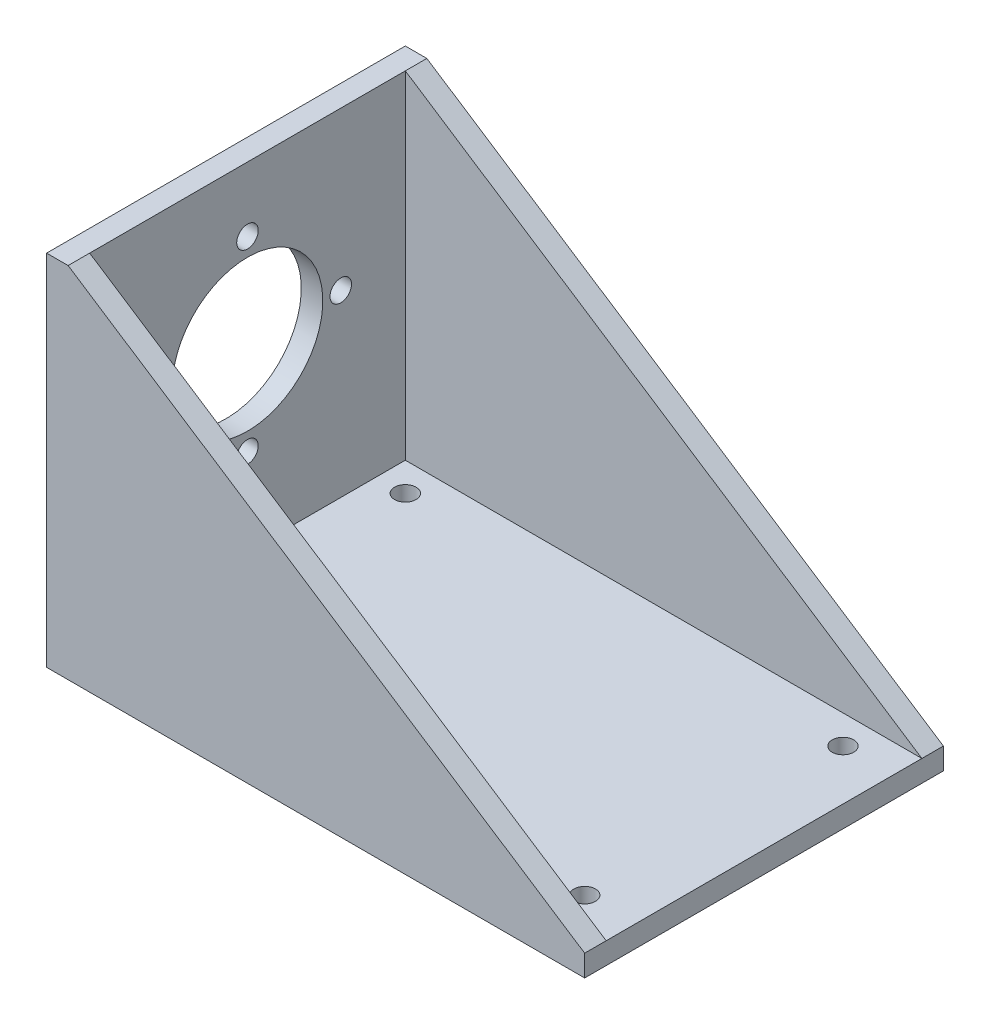
SolidWorks part; units mm, degrees
material "ABS"
ref_plane "Plan de face" through (0, 0, 0) normal (0, 0, 1) x (1, 0, 0)
ref_plane "Plan de dessus" through (0, 0, 0) normal (0, 1, 0) x (1, 0, 0)
ref_plane "Plan de droite" through (0, 0, 0) normal (1, 0, 0) x (0, 0, -1)
sketch "Esquisse1" plane through (0, 0, 0) normal (0, 1, 0) x (1, 0, 0)
  line L1 (0, 0) -> (75, 0)
  line L2 (0, 0) -> (0, 50)
  line L3 (0, 50) -> (75, 50)
  line L4 (75, 0) -> (75, 50)
  dimension "D1" = 50
  dimension "D2" = 75
extrude "Boss.-Extru.1" add sketch "Esquisse1" along normal blind 3
sketch "Esquisse2" plane through (0, 3, 0) normal (0, 1, 0) x (1, 0, 0)
  line L0 (75, 50) -> (0, 50) construction
  line L1 (0, 0) -> (3, 0)
  line L2 (0, 0) -> (0, 50)
  line L3 (0, 50) -> (3, 50)
  line L4 (3, 0) -> (3, 50)
  dimension "D1" = 3
extrude "Boss.-Extru.2" add sketch "Esquisse2" along normal blind 47
sketch "Esquisse3" plane through (0, 0, 0) normal (-1, 0, 0) x (0, 0, 1)
  line L0 (-50, 0) -> (0, 0) construction
  line L1 (0, 50) -> (0, 0) construction
  line L2 (-25, 28) -> (-12, 28) construction
  circle A0 centre (-25, 28) radius 10.5
  circle A1 centre (-12, 28) radius 1.5
  circle A2 centre (-25, 15) radius 1.5
  circle A3 centre (-38, 28) radius 1.5
  circle A4 centre (-25, 41) radius 1.5
  point P17 (-25, 28)
  dimension "D1" = 21
  dimension "D5" = 3
  dimension "D2" = 28
  dimension "D3" = 25
  dimension "D4" = 13
  dimension "D6" = 4
extrude "Enlèv. mat.-Extru.1" cut sketch "Esquisse3" against normal blind 3
sketch "Esquisse4" plane through (0, 0, 0) normal (0, 0, 1) x (1, 0, 0)
  line L0 (3, 50) -> (75, 3)
  line L1 (75, 3) -> (3, 3)
  line L2 (3, 3) -> (3, 50)
extrude "Boss.-Extru.3" add sketch "Esquisse4" against normal blind 3
sketch "Esquisse5" plane through (0, 0, -50) normal (0, 0, -1) x (-1, 0, 0)
  line L0 (-75, 3) -> (-3, 3)
  line L1 (-3, 3) -> (-3, 50)
  line L2 (-3, 50) -> (-75, 3)
extrude "Boss.-Extru.4" add sketch "Esquisse5" against normal blind 3
sketch "Esquisse6" plane through (0, 3, 0) normal (0, 1, 0) x (1, 0, 0)
  line L0 (3, 50) -> (75, 50) construction
  line L1 (75, 0) -> (3, 0) construction
  line L2 (0, 50) -> (0, 0) construction
  line L3 (75, 3) -> (75, 47) construction
  line L4 (75, 0) -> (75, 3) construction
  circle A0 centre (7, 43) radius 1.5
  circle A1 centre (68, 43) radius 1.5
  circle A2 centre (68, 7) radius 1.5
  circle A3 centre (7, 7) radius 1.5
  dimension "D1" = 3
  dimension "D2" = 3
  dimension "D3" = 3
  dimension "D4" = 3
  dimension "D5" = 7
  dimension "D6" = 7
  dimension "D7" = 7
  dimension "D8" = 7
  dimension "D9" = 7
  dimension "D10" = 7
  dimension "D11" = 7
  dimension "D12" = 7
extrude "Enlèv. mat.-Extru.2" cut sketch "Esquisse6" against normal blind 3
